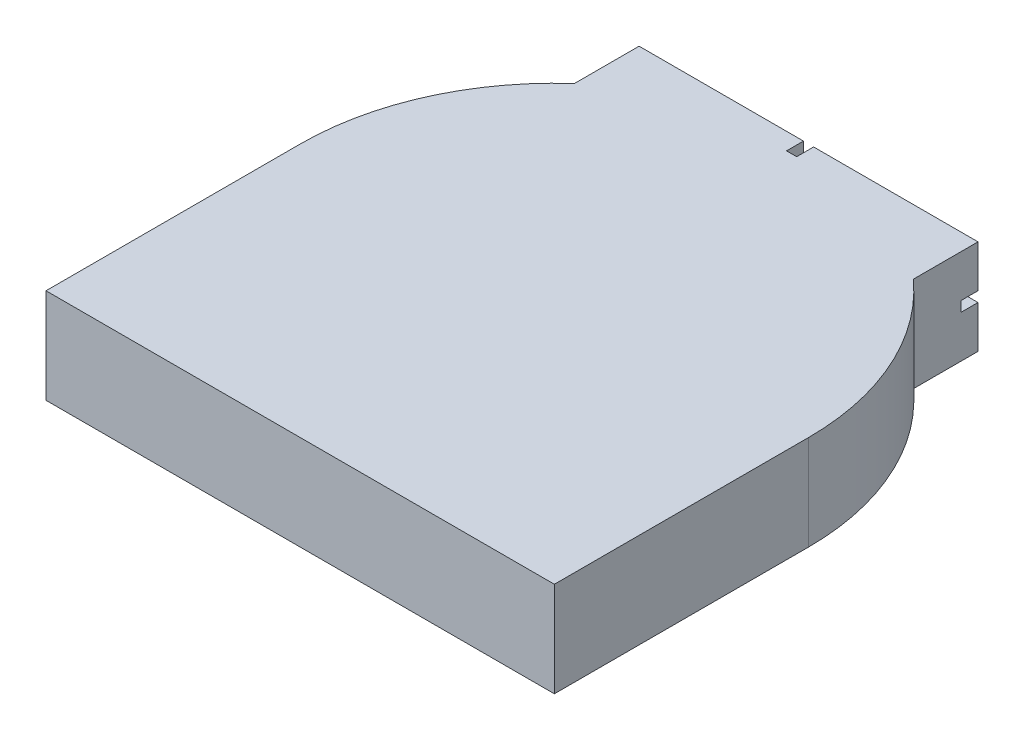
SolidWorks part; units mm, degrees
ref_plane "Front Plane" through (0, 0, 0) normal (0, 0, 1) x (1, 0, 0)
ref_plane "Top Plane" through (0, 0, 0) normal (0, 1, 0) x (1, 0, 0)
ref_plane "Right Plane" through (0, 0, 0) normal (1, 0, 0) x (0, 0, -1)
sketch "Sketch1" plane through (0, 0, 0) normal (0, 1, 0) x (1, 0, 0)
  line L0 (-5, 7.5) -> (-5, 5.5902)
  line L2 (-3, 5.5) -> (-3, 5.1235)
  line L4 (3, 5.5) -> (3, 5.1235)
  line L5 (5, 7.5) -> (5, 5.5902)
  line L6 (-5, 7.5) -> (-3, 7.5)
  line L7 (-3, 5.5) -> (-3, 7.5)
  line L8 (3, 5.5) -> (3, 7.5)
  line L9 (3, 7.5) -> (5, 7.5)
  line L10 (-5, 7.5) -> (5, 7.5) construction
  line L11 (-3, 5.5) -> (3, 5.5) construction
  line L12 (-7.5, 0) -> (-7.5, -7.5)
  line L13 (-7.5, -7.5) -> (7.5, -7.5)
  line L14 (7.5, -7.5) -> (7.5, 0)
  arc A0 (-3.3846, 4.3352) -> (3.3846, 4.3352) centre (0, 0) ccw
  arc A1 (-3.3846, 4.3352) -> (-3, 5.1235) centre (-4, 5.1235) ccw
  arc A2 (3.3846, 4.3352) -> (3, 5.1235) centre (4, 5.1235) cw
  arc A3 (-5, 5.5902) -> (-5, 5.5902) centre (-5, 5.5902) ccw
  arc A4 (-5, 5.5902) -> (-7.5, 0) centre (0, 0) ccw
  arc A5 (5, 5.5902) -> (5, 5.5902) centre (5, 5.5902) cw
  arc A6 (7.5, 0) -> (5, 5.5902) centre (0, 0) ccw
  arc A7 (-5, 5.5902) -> (5, 5.5902) centre (0, 0) ccw construction
  point P19 (-7.5, 0)
  point P22 (7.5, 0)
  point P23 (0, -7.5)
  dimension "D1" = 11
  dimension "D4" = 1
  dimension "D6" = 1
  dimension "D2" = 6
  dimension "D3" = 3
  dimension "D5" = 7.5
  dimension "D7" = 2
extrude "Boss-Extrude1" add sketch "Sketch1" along normal blind 0.8
sketch "Sketch2" plane through (0, 0.8, 0) normal (0, 1, 0) x (1, 0, 0)
  line L0 (5, 5.5902) -> (5, 7.5) construction
  line L1 (5, 7.5) -> (3, 7.5) construction
  line L2 (-5, 7.5) -> (-5, 5.5902) construction
  line L3 (-3, 7.5) -> (-5, 7.5) construction
  line L4 (5, 5.5902) -> (5, 7.5)
  line L5 (5, 7.5) -> (3, 7.5)
  line L6 (-5, 7.5) -> (-5, 5.5902)
  line L7 (-3, 7.5) -> (-5, 7.5)
  line L8 (-3, 7.5) -> (3, 7.5)
  line L9 (7.5, -7.5) -> (7.5, 0) construction
  line L10 (-7.5, -7.5) -> (7.5, -7.5) construction
  line L11 (-7.5, 0) -> (-7.5, -7.5) construction
  line L12 (7.5, -7.5) -> (7.5, 0)
  line L13 (-7.5, -7.5) -> (7.5, -7.5)
  line L14 (-7.5, 0) -> (-7.5, -7.5)
  arc A2 (7.5, 0) -> (5, 5.5902) centre (0, 0) ccw construction
  arc A3 (-5, 5.5902) -> (-7.5, 0) centre (0, 0) ccw construction
  arc A4 (7.5, 0) -> (5, 5.5902) centre (0, 0) ccw
  arc A5 (-5, 5.5902) -> (-7.5, 0) centre (0, 0) ccw
extrude "Boss-Extrude2" add sketch "Sketch2" along normal blind 1
sketch "Sketch3" plane through (0, 0, 0) normal (0, -1, 0) x (1, 0, 0)
  line L0 (-3, -7.5) -> (-5, -7.5) construction
  line L1 (5, -7.5) -> (3, -7.5) construction
  line L2 (5, -5.5902) -> (5, -7.5) construction
  line L3 (-5, -7.5) -> (-5, -5.5902) construction
  line L4 (-3, -7.5) -> (-5, -7.5)
  line L5 (5, -7.5) -> (3, -7.5)
  line L6 (5, -5.5902) -> (5, -7.5)
  line L7 (-5, -7.5) -> (-5, -5.5902)
  line L8 (-3, -7.5) -> (3, -7.5)
  line L9 (-7.5, 0) -> (-7.5, 7.5) construction
  line L10 (-7.5, 7.5) -> (7.5, 7.5) construction
  line L11 (7.5, 7.5) -> (7.5, 0) construction
  line L12 (-7.5, 0) -> (-7.5, 7.5)
  line L13 (-7.5, 7.5) -> (7.5, 7.5)
  line L14 (7.5, 7.5) -> (7.5, 0)
  arc A2 (-7.5, 0) -> (-5, -5.5902) centre (0, 0) ccw construction
  arc A3 (5, -5.5902) -> (7.5, 0) centre (0, 0) ccw construction
  arc A4 (-7.5, 0) -> (-5, -5.5902) centre (0, 0) ccw
  arc A5 (5, -5.5902) -> (7.5, 0) centre (0, 0) ccw
extrude "Boss-Extrude3" add sketch "Sketch3" along normal blind 1
sketch "Sketch4" plane through (0, 0, -7.5) normal (0, 0, -1) x (-1, 0, 0)
  line L0 (-5, 1.8) -> (-5, -1) construction
  line L3 (-5, 1.8) -> (-5, -1) construction
  line L4 (-5, 0.55) -> (-0.15, 0.55)
  line L5 (-5, 0.55) -> (-5, 0.25)
  line L6 (-5, 0.25) -> (-0.15, 0.25)
  line L7 (5, 0.55) -> (5, 0.25)
  line L8 (5, 1.8) -> (5, -1) construction
  line L9 (-3, 0.8) -> (3, 0.8) construction
  line L10 (-5, 1.8) -> (5, 1.8) construction
  line L11 (-0.15, 1.8) -> (0.15, 1.8)
  line L12 (-0.15, 1.8) -> (-0.15, 0.55)
  line L13 (-0.15, -1) -> (0.15, -1)
  line L14 (0.15, 1.8) -> (0.15, 0.55)
  line L15 (5, -1) -> (-5, -1) construction
  line L16 (0.15, 0.55) -> (5, 0.55)
  line L17 (0.15, 0.25) -> (5, 0.25)
  line L18 (0.15, 0.25) -> (0.15, -1)
  line L19 (-0.15, 0.25) -> (-0.15, -1)
  point P0 (-5, 0.4)
  point P1 (0, 0.8)
  dimension "D1" = 0.3
  dimension "D2" = 0.15
  dimension "D3" = 0.3
  dimension "D4" = 0.15
extrude "Cut-Extrude1" cut sketch "Sketch4" against normal blind 0.5
ref_plane "Plane1" through (0, 0.4, 0) normal (0, -1, 0) x (-1, 0, 0)
